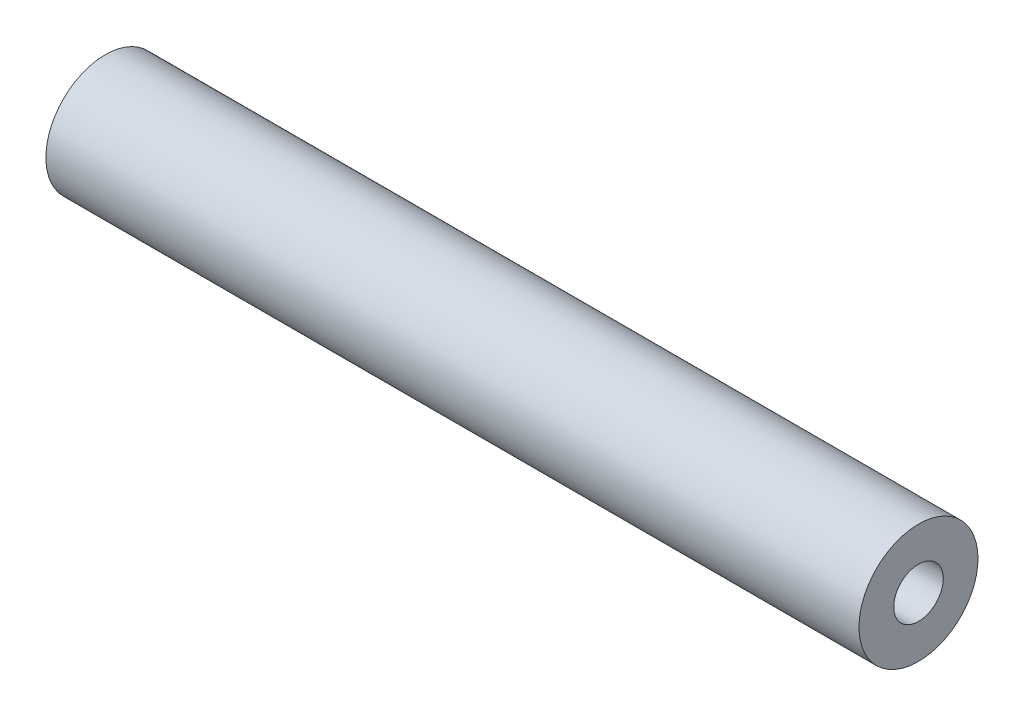
SolidWorks part; units mm, degrees
material "AISI 1020"
ref_plane "Front Plane" through (0, 0, 0) normal (0, 0, 1) x (1, 0, 0)
ref_plane "Top Plane" through (0, 0, 0) normal (0, 1, 0) x (1, 0, 0)
ref_plane "Right Plane" through (0, 0, 0) normal (1, 0, 0) x (0, 0, -1)
sketch "Sketch1" plane through (0, 0, 0) normal (0, 1, 0) x (1, 0, 0)
  line L0 (0, 0) -> (-17.1796, 0) construction
  line L1 (0, 0) -> (41, 0)
  line L2 (0, 0) -> (0, 3)
  line L3 (0, 3) -> (41, 3)
  line L4 (41, 0) -> (41, 3)
  dimension "D1" = 41
  dimension "D2" = 6
revolve "Revolve1" add sketch "Sketch1" angle 360 about L0
cosmetic thread "Cosmetic Thread1" parameters "D1"=10, "D2"=5
sketch "Sketch2" plane through (41, 0, 0) normal (1, 0, 0) x (0, 0, -1)
  circle A0 centre (0, 0) radius 1.25
  dimension "D1" = 2.5
extrude "Cut-Extrude1" cut sketch "Sketch2" against normal blind 10
cosmetic thread "Cosmetic Thread2" parameters "D1"=10, "D2"=3
